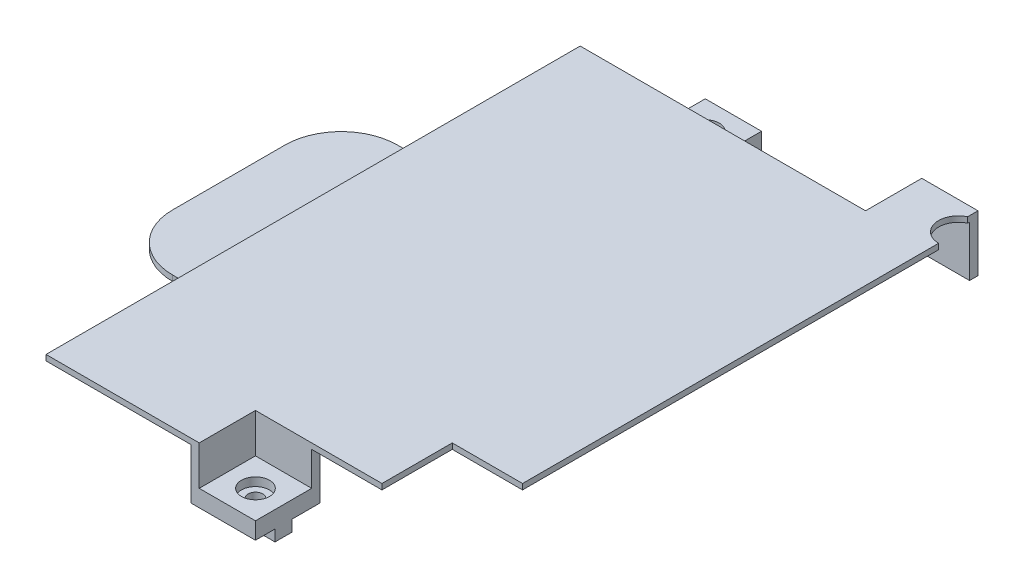
SolidWorks part; units mm, degrees
ref_plane "前视基准面" through (0, 0, 0) normal (0, 0, 1) x (1, 0, 0)
ref_plane "上视基准面" through (0, 0, 0) normal (0, 1, 0) x (1, 0, 0)
ref_plane "右视基准面" through (0, 0, 0) normal (1, 0, 0) x (0, 0, -1)
other "Configuration Table"
sketch "草图1" plane through (0, 0, 0) normal (0, 1, 0) x (1, 0, 0)
  line L5 (-90, -85) -> (90, -85)
  line L6 (-90, -85) -> (-90, 85)
  line L7 (-90, 85) -> (90, 85)
  line L8 (90, -85) -> (90, 85)
extrude "凸台-拉伸1" add sketch "草图1" along normal blind 2 contours L6 L5 L8 L7
sketch "草图2" plane through (0, 0, 0) normal (0, 1, 0) x (1, 0, 0)
  line L0 (90, -85) -> (90, 85) construction
  line L1 (-90, 85) -> (90, 85)
  line L2 (-90, 85) -> (-90, 83)
  line L3 (-90, 83) -> (90, 83)
  line L4 (90, 85) -> (90, 83)
  line L5 (88, -83) -> (-88, -83)
  line L6 (-90, -85) -> (-88, -85)
  line L7 (-90, -85) -> (-90, 83)
  line L8 (-90, 83) -> (-88, 83)
  line L9 (-88, -85) -> (-88, 83)
  line L10 (90, -85) -> (-88, -85)
  line L11 (90, -85) -> (90, -83)
  line L13 (-88, -85) -> (-88, -83)
  line L14 (90, 83) -> (88, 83)
  line L15 (90, 83) -> (90, -83)
  line L16 (90, -83) -> (88, -83)
  line L17 (88, 83) -> (88, -83)
extrude "凸台-拉伸2" add sketch "草图2" against normal blind 18 contours L4 L1 L2 L3 | L6 L9 L3 L7 | L3 L17 L16 L15 | L11 L16 L5 L9 L10
sketch "草图4" plane through (0, 2, 0) normal (0, 1, 0) x (1, 0, 0)
  line L0 (0, 0) -> (0, -85)
  line L1 (-90, -85) -> (90, -85) construction
  line L2 (0, 0) -> (-90, 0)
  line L3 (-90, -85) -> (-90, 85) construction
  line L5 (-110, 0) -> (-110, 10)
  line L6 (-90, 0) -> (-90, -10)
  line L7 (-10, -95) -> (-10, -85)
  line L8 (10, -95) -> (10, -105)
  line L9 (-10, -85) -> (10, -85)
  line L10 (-10, -85) -> (-10, -105)
  line L11 (-10, -105) -> (10, -105)
  line L12 (10, -85) -> (10, -105)
  line L14 (-110, 10) -> (-90, 10)
  line L15 (-110, 10) -> (-110, -10)
  line L16 (-110, -10) -> (-90, -10)
  line L17 (-90, 10) -> (-90, -10)
  line M17 (-90, -85) -> (90, -85)
extrude "凸台-拉伸3" add sketch "草图4" against normal blind 20 contours L12 L7 L10 L11 L8 M17 | L15 L14 L17 L16
sketch "草图5" plane through (0, 2, 0) normal (0, 1, 0) x (1, 0, 0)
  line L1 (-110, 10) -> (-90, 10)
  line L2 (-110, 10) -> (-110, -10)
  line L3 (-110, -10) -> (-90, -10)
  line L4 (-90, 10) -> (-90, -10)
  line L5 (-10, -85) -> (10, -85)
  line L6 (-10, -85) -> (-10, -105)
  line L7 (-10, -105) -> (10, -105)
  line L8 (10, -85) -> (10, -105)
extrude "切除-拉伸1" cut sketch "草图5" against normal blind 14 contours L6 L5 L8 L7 | L2 L1 L4 L3
sketch "草图6" plane through (0, 0, 0) normal (0, -1, 0) x (1, 0, 0)
  line L0 (88, 83) -> (88, 82)
  line L2 (-88, -83) -> (-88, 83)
  line L3 (-88, 83) -> (88, 83)
  line L4 (88, -83) -> (88, 83)
  line L6 (-88, -83) -> (-87, -83)
  line L8 (-88, -83) -> (88, -83)
  line L9 (-87, -82) -> (87, -82)
  line L10 (-87, -82) -> (-87, 82)
  line L11 (-87, 82) -> (87, 82)
  line L12 (87, -82) -> (87, 82)
  line M13 (-88, -83) -> (88, -83)
  line M14 (88, -83) -> (88, 83)
  line M15 (88, 83) -> (-88, 83)
  line M16 (-88, 83) -> (-88, -83)
extrude "凸台-拉伸4" add sketch "草图6" along normal blind 18 contours L12 L9 L10 L11 M16 M13 M14 M15
sketch "草图7" plane through (0, -18, 0) normal (0, -1, 0) x (-1, 0, 0)
  line L0 (0, 0) -> (0, 85)
  line L1 (90, 85) -> (-90, 85) construction
  line L3 (0, 105) -> (-10, 105)
  line L4 (0, 85) -> (10, 85)
  line L6 (10, 85) -> (-10, 85)
  line L7 (10, 85) -> (10, 105)
  line L8 (10, 105) -> (-10, 105)
  line L9 (-10, 85) -> (-10, 105)
extrude "凸台-拉伸5" add sketch "草图7" against normal blind 6 contours L7 L6 L9 L8
sketch "草图8" plane through (0, -18, 0) normal (0, -1, 0) x (-1, 0, 0)
  line L0 (-87, -82) -> (-90, -82)
  line L1 (-90, 85) -> (-90, -85) construction
  line L2 (-87, 82) -> (-90, 82)
  line L4 (-87, 82) -> (-90, 82)
  line L5 (-87, 82) -> (-87, -85)
  line L6 (-87, -85) -> (-90, -85)
  line L7 (-90, 82) -> (-90, -85)
  line M5 (-90, 85) -> (-90, -85)
  line M6 (-90, -85) -> (-10, -85)
  line M21 (-87, -82) -> (-87, 82)
extrude "切除-拉伸2" cut sketch "草图8" against normal blind 18 contours L2 L0 M21 M5 | L5 L0 M5 M6
sketch "草图9" plane through (0, -18, 0) normal (0, -1, 0) x (-1, 0, 0)
  line L0 (10, -105) -> (10, -85) construction
  line L1 (-87, -82) -> (-10, -82)
  line L2 (-87, -82) -> (-87, -85)
  line L3 (-87, -85) -> (-10, -85)
  line L4 (-10, -82) -> (-10, -85)
  line L5 (87, -82) -> (10, -82)
  line L6 (87, -82) -> (87, -85)
  line L7 (87, -85) -> (10, -85)
  line L8 (10, -82) -> (10, -85)
  line L9 (90, -85) -> (10, -85) construction
extrude "切除-拉伸3" cut sketch "草图9" against normal blind 18
sketch "草图10" plane through (0, 2, 0) normal (0, 1, 0) x (1, 0, 0)
  line L1 (90, -85) -> (65, -85)
  line L2 (90, -85) -> (90, -60)
  line L3 (90, -60) -> (65, -60)
  line L4 (65, -85) -> (65, -60)
extrude "切除-拉伸4" cut sketch "草图10" against normal blind 18
sketch "草图11" plane through (0, -18, 0) normal (0, -1, 0) x (-1, 0, 0)
  line L0 (0, 95) -> (0, 91.95)
  line L2 (-10, 85) -> (-10, 105) construction
  line L3 (-3.05, 98.05) -> (-10, 98.05)
  line L4 (10, 85) -> (10, 105) construction
  line L5 (10, 95) -> (10, 91.95)
  line L6 (-10, 95) -> (-10, 98.05)
  line L7 (0, 91.95) -> (3.05, 91.95)
  line L9 (10, 91.95) -> (10, 98.05)
  line L11 (-10, 91.95) -> (-10, 98.05)
  line L12 (0, 95) -> (0, 98.05)
  line L13 (0, 98.05) -> (-3.05, 98.05)
  line L14 (-3.05, 98.05) -> (-3.05, 91.95)
  line L15 (-3.05, 91.95) -> (-10, 91.95)
  line L16 (-10, 98.05) -> (-10, 91.95)
  line L17 (3.05, 91.95) -> (10, 91.95)
  line L18 (3.05, 91.95) -> (3.05, 98.05)
  line L19 (3.05, 98.05) -> (10, 98.05)
  line L20 (10, 91.95) -> (10, 98.05)
  line M23 (-10, 105) -> (-10, 85)
extrude "凸台-拉伸6" add sketch "草图11" along normal blind 4 contours L15 L14 L3 M23 | L18 L17 L20 L19
sketch "草图12" plane through (0, -18, 0) normal (0, -1, 0) x (-1, 0, 0)
  line L0 (3.05, 91.95) -> (-3.05, 98.05)
  circle A0 centre (0, 95) radius 2.6
extrude "切除-拉伸5" cut sketch "草图12" against normal blind 6 contours L0 A0 | L0 A0
sketch "草图13" plane through (0, -12, 0) normal (0, 1, 0) x (1, 0, 0)
  circle A0 centre (0, 95) radius 5
  circle M2 centre (0, 95) radius 2.6
extrude "切除-拉伸6" cut sketch "草图13" against normal blind 3 contours A0 M2
sketch "草图14" plane through (0, -12, 0) normal (0, 1, 0) x (1, 0, 0)
  line L0 (-110, -10) -> (-90, 10)
  circle A0 centre (-100, 0) radius 5
extrude "切除-拉伸7" cut sketch "草图14" against normal blind 3 contours L0 A0
sketch "草图15" plane through (0, -15, 0) normal (0, 1, 0) x (1, 0, 0)
  circle A0 centre (-100, 0) radius 2.6
extrude "切除-拉伸8" cut sketch "草图15" against normal blind 3 contours A0
sketch "草图16" plane through (0, -18, 0) normal (0, -1, 0) x (1, 0, 0)
  line L0 (-100, 0) -> (-100, 3.05)
  line L1 (-100, 0) -> (-100, -3.05)
  line L2 (-100, -3.05) -> (-96.95, -3.05)
  line L3 (-100, 3.05) -> (-103.05, 3.05)
  line L4 (-96.95, -3.05) -> (-96.95, 10)
  line L5 (-110, 10) -> (-90, 10) construction
  line L6 (-103.05, 3.05) -> (-103.05, -10)
  line L7 (-110, -10) -> (-90, -10) construction
  line L9 (-103.05, 3.05) -> (-96.95, 3.05)
  line L10 (-103.05, 3.05) -> (-103.05, 10)
  line L11 (-103.05, 10) -> (-96.95, 10)
  line L12 (-96.95, 3.05) -> (-96.95, 10)
  line L13 (-96.95, -3.05) -> (-103.05, -3.05)
  line L14 (-96.95, -3.05) -> (-96.95, -10)
  line L15 (-96.95, -10) -> (-103.05, -10)
  line L16 (-103.05, -3.05) -> (-103.05, -10)
  line M28 (-110, -10) -> (-90, -10)
extrude "凸台-拉伸7" add sketch "草图16" along normal blind 4 contours L14 L2 L13 L6 M28 | L10 L9 L12 L11
sketch "草图17" plane through (0, -18, 0) normal (0, -1, 0) x (-1, 0, 0)
  line L0 (-10, -85) -> (10, -105)
  circle A0 centre (0, -95) radius 2.6
extrude "切除-拉伸9" cut sketch "草图17" against normal blind 6 contours L0 A0 | L0 A0
sketch "草图18" plane through (0, -12, 0) normal (0, 1, 0) x (1, 0, 0)
  circle A0 centre (0, -95) radius 5
  circle M2 centre (0, -95) radius 2.6
extrude "切除-拉伸10" cut sketch "草图18" against normal blind 3 contours A0 M2
sketch "草图19" plane through (0, -18, 0) normal (0, -1, 0) x (-1, 0, 0)
  line L0 (0, -95) -> (-3.05, -95)
  line L1 (-3.05, -95) -> (-3.05, -98.05)
  line L2 (0, -95) -> (3.05, -95)
  line L3 (3.05, -95) -> (3.05, -91.95)
  line L4 (3.05, -91.95) -> (-10, -91.95)
  line L5 (-10, -82) -> (-10, -105) construction
  line L6 (-3.05, -98.05) -> (10, -98.05)
  line L7 (10, -105) -> (10, -82) construction
  line L9 (10, -98.05) -> (3.05, -98.05)
  line L10 (10, -98.05) -> (10, -91.95)
  line L11 (10, -91.95) -> (3.05, -91.95)
  line L12 (3.05, -98.05) -> (3.05, -91.95)
  line L13 (-3.05, -98.05) -> (-10, -98.05)
  line L14 (-3.05, -98.05) -> (-3.05, -91.95)
  line L15 (-3.05, -91.95) -> (-10, -91.95)
  line L16 (-10, -98.05) -> (-10, -91.95)
  line M7 (-10, -82) -> (-10, -105)
  line M9 (10, -105) -> (10, -82)
extrude "凸台-拉伸8" add sketch "草图19" along normal blind 4 contours L12 L6 L11 L3 M9 | L1 L14 L4 L13 M7
sketch "草图20" plane through (0, 2, 0) normal (0, 1, 0) x (1, 0, 0)
  line L0 (-90, -85) -> (-10, -85)
  line L1 (-10, -85) -> (10, -85)
  line L2 (10, -85) -> (40, -85)
  line L4 (-90, -85) -> (-10, -85)
  line L5 (-90, -85) -> (-90, -105)
  line L6 (-90, -105) -> (-10, -105)
  line L7 (-10, -85) -> (-10, -105)
  line L8 (40, -85) -> (10, -85)
  line L9 (40, -85) -> (40, -105)
  line L10 (40, -105) -> (10, -105)
  line L11 (10, -85) -> (10, -105)
  line M11 (-90, -85) -> (65, -85)
extrude "凸台-拉伸9" add sketch "草图20" against normal blind 2 contours L11 L10 L9 M11 | L5 L4 L7 L6
sketch "草图21" plane through (0, 0, 0) normal (0, -1, 0) x (-1, 0, 0)
  line L1 (87, -85) -> (90, -85)
  line L2 (87, -85) -> (87, -105)
  line L3 (87, -105) -> (90, -105)
  line L4 (90, -85) -> (90, -105)
extrude "凸台-拉伸10" add sketch "草图21" along normal blind 18
sketch "草图22" plane through (0, -12, 0) normal (0, 1, 0) x (1, 0, 0)
  line L1 (-10, -105) -> (10, -105)
  line L2 (-10, -105) -> (-10, -85)
  line L3 (-10, -85) -> (10, -85)
  line L4 (10, -105) -> (10, -85)
  circle A0 centre (0, -95) radius 5
extrude "凸台-拉伸11" add sketch "草图22" along normal blind 14 contours L2 L1 L4 L3
sketch "草图23" plane through (0, 0, 0) normal (0, -1, 0) x (-1, 0, 0)
  line L1 (-10, -105) -> (-40, -105)
  line L2 (-10, -105) -> (-10, -85)
  line L3 (-10, -85) -> (-40, -85)
  line L4 (-40, -105) -> (-40, -85)
  line M12 (-40, -85) -> (-40, -105)
  line M13 (-40, -105) -> (-10, -105)
  line M14 (-10, -105) -> (-10, -82)
extrude "切除-拉伸11" cut sketch "草图23" against normal blind 14 contours L3 M14 M12 M13
sketch "草图24" plane through (0, 2, 0) normal (0, 1, 0) x (1, 0, 0)
  line L1 (90, 85) -> (70, 85)
  line L2 (90, 85) -> (90, 105)
  line L3 (90, 105) -> (70, 105)
  line L4 (70, 85) -> (70, 105)
extrude "凸台-拉伸12" add sketch "草图24" against normal blind 2 contours L2 L1 L4 L3
sketch "草图25" plane through (0, -18, 0) normal (0, -1, 0) x (-1, 0, 0)
  line L1 (-70, 85) -> (-90, 85)
  line L2 (-70, 85) -> (-70, 82)
  line L3 (-70, 82) -> (-90, 82)
  line L4 (-90, 85) -> (-90, 82)
extrude "切除-拉伸12" cut sketch "草图25" against normal blind 18
sketch "草图26" plane through (0, 0, 0) normal (0, -1, 0) x (1, 0, 0)
  line L0 (70, -85) -> (90, -85)
  line L1 (90, -105) -> (90, 60) construction
  line L2 (90, -102) -> (90, -95)
  line L3 (90, -95) -> (90, -88)
  arc A0 (90, -88) -> (90, -102) centre (90, -95) ccw
  line M14 (90, -105) -> (90, 60)
extrude "切除-拉伸13" cut sketch "草图26" against normal blind 18 contours A0 M14
sketch "草图27" plane through (0, 2, 0) normal (0, 1, 0) x (1, 0, 0)
  line L1 (70, 85) -> (67, 85)
  line L2 (70, 85) -> (70, 105)
  line L3 (70, 105) -> (67, 105)
  line L4 (67, 85) -> (67, 105)
extrude "凸台-拉伸13" add sketch "草图27" against normal blind 20 contours L2 L1 L4 L3
sketch "草图28" plane through (0, 2, 0) normal (0, 1, 0) x (1, 0, 0)
  line L1 (90, 102) -> (67, 102)
  line L2 (90, 102) -> (90, 105)
  line L3 (90, 105) -> (67, 105)
  line L4 (67, 102) -> (67, 105)
extrude "凸台-拉伸14" add sketch "草图28" against normal blind 20 contours L2 L1 L4 L3
sketch "草图29" plane through (0, 2, 0) normal (0, 1, 0) x (1, 0, 0)
  line L1 (90, 105) -> (87, 105)
  line L2 (90, 105) -> (90, 100)
  line L3 (90, 100) -> (87, 100)
  line L4 (87, 105) -> (87, 100)
extrude "切除-拉伸14" cut sketch "草图29" against normal blind 20 contours L2 L1 L4 L3
sketch "草图30" plane through (0, 2, 0) normal (0, 1, 0) x (1, 0, 0)
  line L0 (67, 85) -> (90, 85)
  line L1 (90, -60) -> (90, 88) construction
  line L2 (90, 85) -> (-34.5, 85)
  line L3 (-90, 85) -> (67, 85) construction
  line L4 (-34.5, 85) -> (-34.5, 40)
  line L5 (-34.5, 40) -> (-54.5, 40)
  line L6 (-34.5, 85) -> (-90, 85)
  line L7 (-90, 85) -> (-90, 10)
  line L8 (-74.5, 20) -> (-74.5, -20)
  line L9 (-54.5, -40) -> (-34.5, -40)
  line L10 (-34.5, -40) -> (-34.5, -85)
  line L11 (-90, 10) -> (-110, 10)
  line L12 (-110, 10) -> (-110, -10)
  line L13 (-110, -10) -> (-90, -10)
  line L14 (-90, -105) -> (-90, 85) construction
  line L15 (-90, -10) -> (-90, -105)
  line L16 (-90, -105) -> (-34.5, -105)
  line L17 (10, -105) -> (-90, -105) construction
  line L18 (-34.5, -105) -> (-34.5, -85)
  arc A0 (-54.5, 40) -> (-74.5, 20) centre (-54.5, 20) ccw
  arc A1 (-74.5, -20) -> (-54.5, -40) centre (-54.5, -20) ccw
  line M22 (67, 85) -> (-90, 85)
  line M23 (-90, 85) -> (-90, -105)
  line M24 (-90, -105) -> (10, -105)
extrude "切除-拉伸15" cut sketch "草图30" against normal blind 30 contours A1 L8 A0 L5 L4 L18 L10 L9 M22 M23 M24 | L12 L13 L11 M23
sketch "草图31" plane through (0, 2, 0) normal (0, 1, 0) x (1, 0, 0)
  line L0 (10, -105) -> (-34.5, -105) construction
  line L1 (-34.5, 85) -> (-31.5, 85)
  line L2 (-34.5, 85) -> (-34.5, -105)
  line L3 (-34.5, -105) -> (-31.5, -105)
  line L4 (-31.5, 85) -> (-31.5, -105)
extrude "凸台-拉伸15" add sketch "草图31" against normal blind 20 contours L2 L1 L4 L3
sketch "草图32" plane through (0, -18, 0) normal (0, -1, 0) x (-1, 0, 0)
  line L0 (34.5, -40) -> (54.5, -40)
  line L3 (54.5, 40) -> (34.5, 40)
  line L4 (34.5, 40) -> (34.5, -40)
  line L5 (74.5, -20) -> (74.5, 20)
  arc A0 (54.5, -40) -> (74.5, -20) centre (54.5, -20) ccw
  arc A1 (74.5, 20) -> (54.5, 40) centre (54.5, 20) ccw
extrude "凸台-拉伸16" add sketch "草图32" against normal blind 2 contours A0 L5 A1 L3 L4 L0
sketch "草图33" plane through (0, 2, 0) normal (0, 1, 0) x (1, 0, 0)
  line L1 (-34.5, -40) -> (-74.5, -40)
  line L2 (-34.5, -40) -> (-34.5, 40)
  line L3 (-34.5, 40) -> (-74.5, 40)
  line L4 (-74.5, -40) -> (-74.5, 40)
extrude "切除-拉伸16" cut sketch "草图33" against normal blind 2 contours L2 L1 L4 L3
sketch "草图34" plane through (0, 2, 0) normal (0, 1, 0) x (1, 0, 0)
  line L1 (10, -85) -> (-34.5, -85)
  line L2 (10, -85) -> (10, -105)
  line L3 (10, -105) -> (-34.5, -105)
  line L4 (-34.5, -85) -> (-34.5, -105)
extrude "切除-拉伸17" cut sketch "草图34" against normal blind 30
sketch "草图35" plane through (0, -18, 0) normal (0, -1, 0) x (-1, 0, 0)
  line L1 (10, -82) -> (-10, -82)
  line L2 (10, -82) -> (10, -85)
  line L3 (10, -85) -> (-10, -85)
  line L4 (-10, -82) -> (-10, -85)
extrude "切除-拉伸18" cut sketch "草图35" against normal blind 18 contours L2 L1 L4 L3
sketch "草图36" plane through (0, 2, 0) normal (0, 1, 0) x (1, 0, 0)
  line L0 (90, -60) -> (90, -85)
  line L1 (65, -85) -> (90, -85)
  line L2 (90, -85) -> (90, -105)
  line L3 (90, -105) -> (40, -105)
  line L4 (40, -105) -> (40, -85)
  line L5 (-34.5, -85) -> (65, -85) construction
  line L7 (20, -85) -> (20, -105)
  line L8 (20, -105) -> (40, -105)
  line L11 (20, -85) -> (20, -82)
  line L12 (20, -82) -> (40, -82)
  line L13 (40, -85) -> (40, -82)
extrude "凸台-拉伸17" add sketch "草图36" against normal blind 20 contours L4 L13 L12 L11 L7 L8
sketch "草图37" plane through (0, 2, 0) normal (0, 1, 0) x (1, 0, 0)
  line L0 (20, -85) -> (40, -105)
  circle A0 centre (30, -95) radius 2.6
extrude "切除-拉伸19" cut sketch "草图37" against normal blind 20 contours L0 A0 | L0 A0
sketch "草图38" plane through (0, 2, 0) normal (0, 1, 0) x (1, 0, 0)
  circle A0 centre (30, -95) radius 5
extrude "切除-拉伸20" cut sketch "草图38" against normal blind 17 contours A0
sketch "草图39" plane through (0, 2, 0) normal (0, 1, 0) x (1, 0, 0)
  line L1 (20, -85) -> (40, -85)
  line L2 (20, -85) -> (20, -105)
  line L3 (20, -105) -> (40, -105)
  line L4 (40, -85) -> (40, -105)
  circle A0 centre (30, -95) radius 5
extrude "切除-拉伸21" cut sketch "草图39" against normal blind 14 contours L2 L1 L4 L3
sketch "草图40" plane through (0, 2, 0) normal (0, 1, 0) x (1, 0, 0)
  line L1 (-34.5, -85) -> (20, -85)
  line L2 (-34.5, -85) -> (-34.5, -105)
  line L3 (-34.5, -105) -> (20, -105)
  line L4 (20, -85) -> (20, -105)
extrude "凸台-拉伸18" add sketch "草图40" against normal blind 2
sketch "草图42" plane through (0, -18, 0) normal (0, -1, 0) x (-1, 0, 0)
  line L0 (34.5, -105) -> (-20, -105) construction
  line L1 (-20, -82) -> (-17, -82)
  line L2 (-20, -82) -> (-20, -105)
  line L3 (-20, -105) -> (-17, -105)
  line L4 (-17, -82) -> (-17, -105)
extrude "凸台-拉伸20" add sketch "草图42" against normal blind 18 contours L2 L1 L4 L3
sketch "草图44" plane through (0, -18, 0) normal (0, -1, 0) x (-1, 0, 0)
  line L0 (-30, -95) -> (-30, -98.05)
  line L1 (-30, -98.05) -> (-33.05, -98.05)
  line L2 (-30, -95) -> (-30, -91.95)
  line L3 (-30, -91.95) -> (-26.95, -91.95)
  line L4 (-30, -91.95) -> (-40, -91.95)
  line L5 (-40, -105) -> (-40, -82) construction
  line L6 (-30, -98.05) -> (-17, -98.05)
  line L7 (-17, -82) -> (-17, -105) construction
  line L9 (-17, -98.05) -> (-26.95, -98.05)
  line L10 (-17, -98.05) -> (-17, -91.95)
  line L11 (-17, -91.95) -> (-26.95, -91.95)
  line L12 (-26.95, -98.05) -> (-26.95, -91.95)
  line L13 (-33.05, -98.05) -> (-40, -98.05)
  line L14 (-33.05, -98.05) -> (-33.05, -91.95)
  line L15 (-33.05, -91.95) -> (-40, -91.95)
  line L16 (-40, -98.05) -> (-40, -91.95)
  line M11 (-17, -105) -> (-17, -82)
extrude "凸台-拉伸21" add sketch "草图44" along normal blind 4 contours L12 L6 L11 M11 | L14 L13 L16 L15
